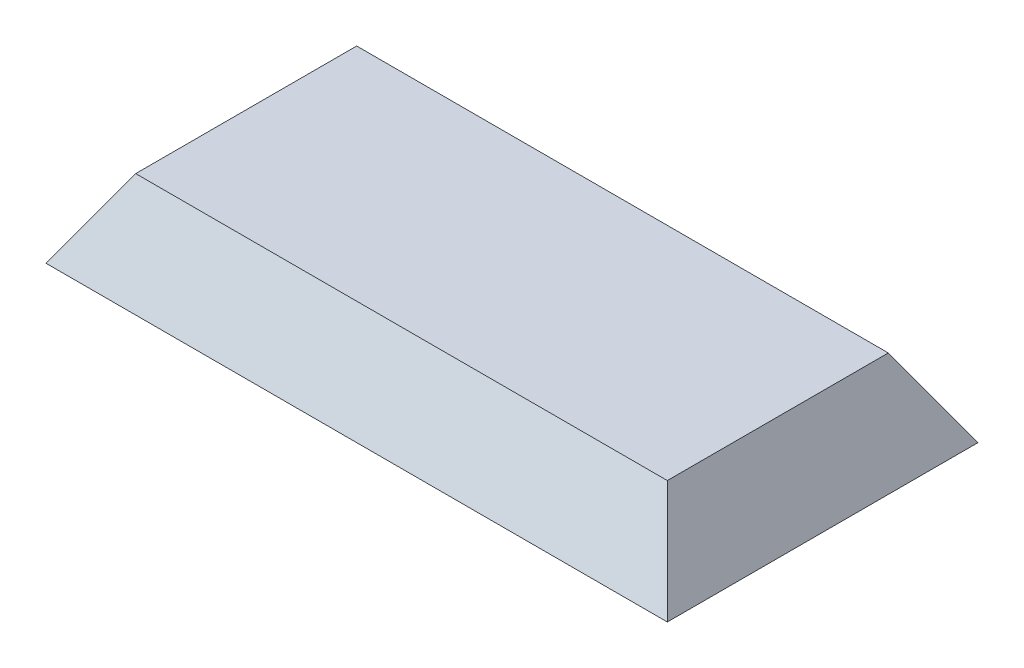
SolidWorks part; units mm, degrees
ref_plane "Front Plane" through (0, 0, 0) normal (0, 0, 1) x (1, 0, 0)
ref_plane "Top Plane" through (0, 0, 0) normal (0, 1, 0) x (1, 0, 0)
ref_plane "Right Plane" through (0, 0, 0) normal (1, 0, 0) x (0, 0, -1)
sketch "Sketch1" plane through (0, 0, 0) normal (0, 1, 0) x (1, 0, 0)
  line L1 (-40, -20) -> (40, -20)
  line L2 (-40, -20) -> (-40, 20)
  line L3 (-40, 20) -> (40, 20)
  line L4 (40, -20) -> (40, 20)
  line L5 (-40, -20) -> (40, 20) construction
  line L6 (-40, 20) -> (40, -20) construction
  point P0 (0, 0)
  dimension "D1" = 40
  dimension "D2" = 80
extrude "Boss-Extrude1" add sketch "Sketch1" along normal blind 10 draft 30
